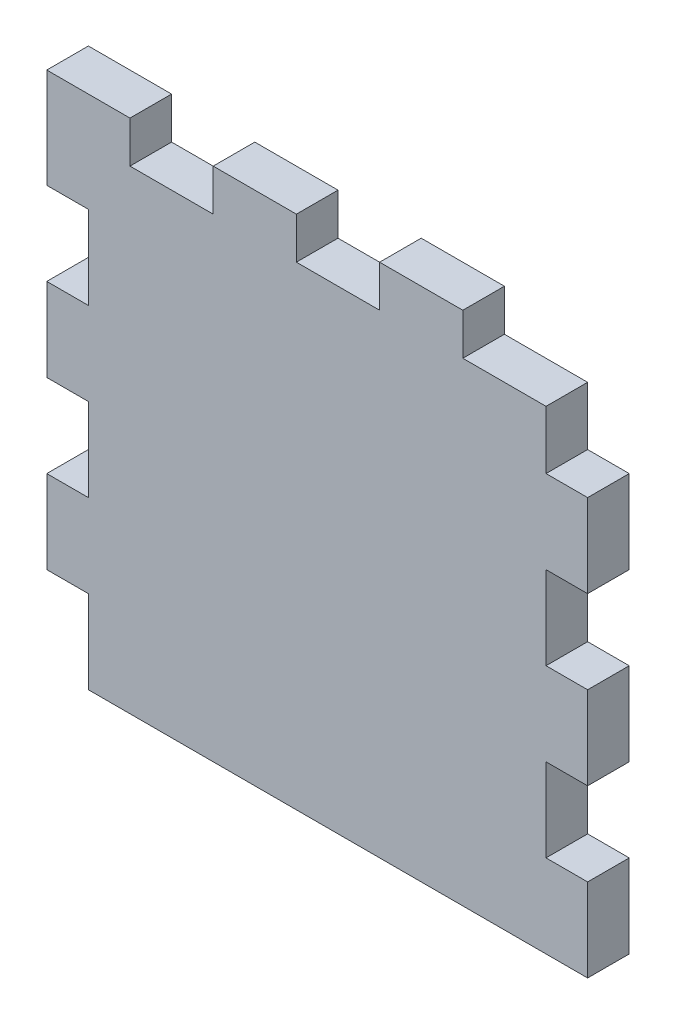
SolidWorks part; units mm, degrees
ref_plane "정면" through (0, 0, 0) normal (0, 0, 1) x (1, 0, 0)
ref_plane "윗면" through (0, 0, 0) normal (0, 1, 0) x (1, 0, 0)
ref_plane "우측면" through (0, 0, 0) normal (1, 0, 0) x (0, 0, -1)
sketch "스케치1" plane through (0, 0, 0) normal (0, 0, 1) x (1, 0, 0)
  line L1 (-30, 28.5) -> (30, 28.5)
  line L2 (-30, 28.5) -> (-30, -28.5)
  line L3 (-30, -28.5) -> (30, -28.5)
  line L4 (30, 28.5) -> (30, -28.5)
  line L5 (-30, 28.5) -> (30, -28.5) construction
  line L6 (-30, -28.5) -> (30, 28.5) construction
  point P0 (0, 0)
  dimension "D1" = 57
  dimension "D2" = 60
extrude "보스-돌출1" add sketch "스케치1" along normal blind 5
sketch "스케치2" plane through (0, 0, 5) normal (0, 0, 1) x (1, 0, 0)
  line L0 (30, -28.5) -> (30, 28.5) construction
  line L5 (30, -18.5) -> (35, -18.5)
  line L6 (30, -18.5) -> (30, -28.5)
  line L7 (30, -28.5) -> (35, -28.5)
  line L8 (35, -18.5) -> (35, -28.5)
  line L10 (-30, -28.5) -> (30, -28.5) construction
  dimension "D2" = 10
  dimension "D3" = 5
extrude "보스-돌출3" add sketch "스케치2" against normal up to surface (5 mm away) up to face at (0, 0, 0)
pattern_linear "선형 패턴2" count 3 spacing 20 along (0, 1, 0) of "보스-돌출3"
sketch "스케치3" plane through (0, 0, 0) normal (0, 0, -1) x (-1, 0, 0)
  line L1 (30, 28.5) -> (20, 28.5)
  line L2 (30, 28.5) -> (30, 33.5)
  line L3 (30, 33.5) -> (20, 33.5)
  line L4 (20, 28.5) -> (20, 33.5)
  dimension "D1" = 5
  dimension "D2" = 10
extrude "보스-돌출4" add sketch "스케치3" against normal up to surface (5 mm away) up to face at (23.5714, 1.0714, 5)
pattern_linear "선형 패턴3" count 3 spacing 20 along (1, 0, 0) of "보스-돌출4"
sketch "스케치4" plane through (0, 0, 0) normal (0, 0, -1) x (-1, 0, 0)
  line L1 (30, -28.5) -> (25, -28.5)
  line L2 (30, -28.5) -> (30, -18.5)
  line L3 (30, -18.5) -> (25, -18.5)
  line L4 (25, -28.5) -> (25, -18.5)
  dimension "D1" = 5
  dimension "D2" = 10
extrude "컷-돌출1" cut sketch "스케치4" against normal up to next
pattern_linear "선형 패턴4" count 3 spacing 20 along (0, 1, 0) of "컷-돌출1"
